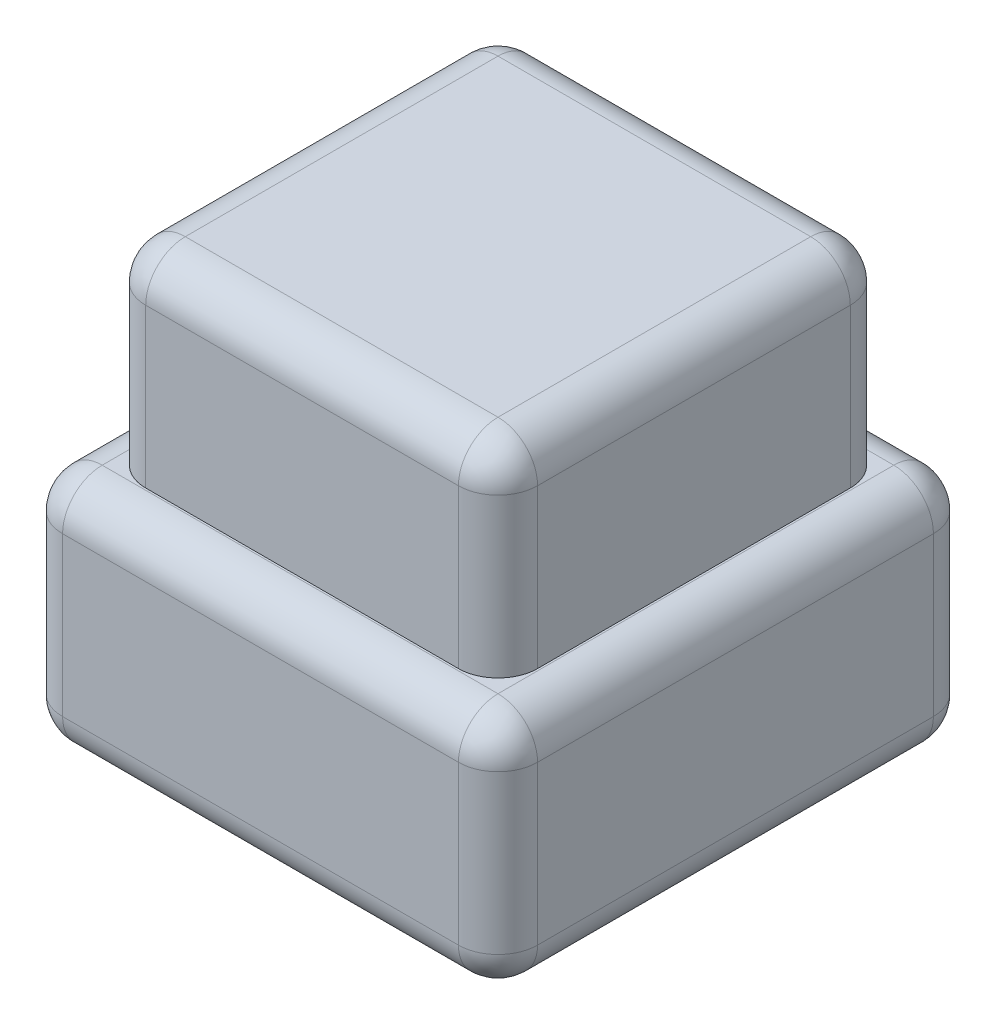
SolidWorks part; units mm, degrees
ref_plane "Front Plane" through (0, 0, 0) normal (0, 0, 1) x (1, 0, 0)
ref_plane "Top Plane" through (0, 0, 0) normal (0, 1, 0) x (1, 0, 0)
ref_plane "Right Plane" through (0, 0, 0) normal (1, 0, 0) x (0, 0, -1)
sketch "Sketch1" plane through (0, 0, 0) normal (0, 1, 0) x (1, 0, 0)
  line L1 (4.95, 4.95) -> (-4.95, 4.95)
  line L2 (4.95, 4.95) -> (4.95, -4.95)
  line L3 (4.95, -4.95) -> (-4.95, -4.95)
  line L4 (-4.95, 4.95) -> (-4.95, -4.95)
  line L5 (4.95, 4.95) -> (-4.95, -4.95) construction
  line L6 (4.95, -4.95) -> (-4.95, 4.95) construction
  point P1 (0, 0)
  dimension "D1" = 9.9
extrude "Boss-Extrude1" add sketch "Sketch1" along normal blind 5
sketch "Sketch2" plane through (0, 0, 0) normal (0, -1, 0) x (1, 0, 0)
  line L1 (-6, -6) -> (6, -6)
  line L2 (-6, -6) -> (-6, 6)
  line L3 (-6, 6) -> (6, 6)
  line L4 (6, -6) -> (6, 6)
  line L5 (-6, -6) -> (6, 6) construction
  line L6 (-6, 6) -> (6, -6) construction
  point P0 (0, 0)
  dimension "D1" = 12
extrude "Boss-Extrude2" add sketch "Sketch2" along normal blind 6
sketch "Sketch3" plane through (0, -6, 0) normal (0, -1, 0) x (1, 0, 0)
  line L1 (2, -2) -> (-2, -2)
  line L2 (2, -2) -> (2, 2)
  line L3 (2, 2) -> (-2, 2)
  line L4 (-2, -2) -> (-2, 2)
  line L5 (2, -2) -> (-2, 2) construction
  line L6 (2, 2) -> (-2, -2) construction
  point P0 (0, 0)
  dimension "D1" = 4
extrude "Cut-Extrude1" cut sketch "Sketch3" against normal blind 3
fillet "Fillet1" radius 1 24 edges at (0, -6, -6) (-6, -6, 0) (0, -6, 6) (6, -6, 0) (2, -6, 0) (-2, -6, 0) (0, -6, -2) (0, -6, 2) (0, 0, -6) (-6, -3, -6) (-6, 0, 0) (-6, -3, 6) (0, 0, 6) (6, 0, 0) (6, -3, -6) (6, -3, 6) (0, 5, -4.95) (4.95, 5, 0) (-4.95, 5, 0) (-4.95, 2.5, 4.95) (-4.95, 2.5, -4.95) (4.95, 2.5, -4.95) (4.95, 2.5, 4.95) (0, 5, 4.95)
